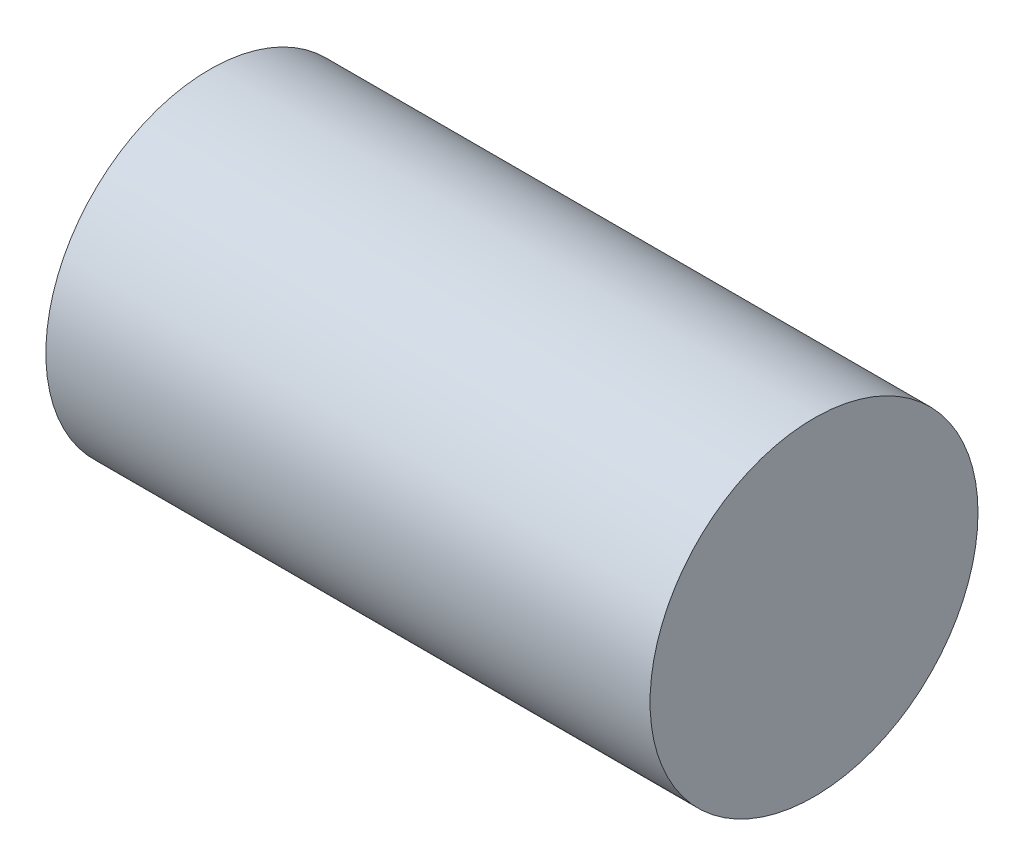
SolidWorks part; units mm, degrees
ref_plane "Front Plane" through (0, 0, 0) normal (1, 0, 0) x (0, 1, 0)
ref_plane "Top Plane" through (0, 0, 0) normal (0, 0, 1) x (0, 1, 0)
ref_plane "Right Plane" through (0, 0, 0) normal (0, 1, 0) x (-1, 0, 0)
sketch "Sketch1" plane through (0, 0, 0) normal (1, 0, 0) x (0, 1, 0)
  circle A0 centre (0, 0) radius 4.98
  dimension "D1" = 9.96
extrude "Boss-Extrude1" add sketch "Sketch1" along normal blind 18.35 contours A0
